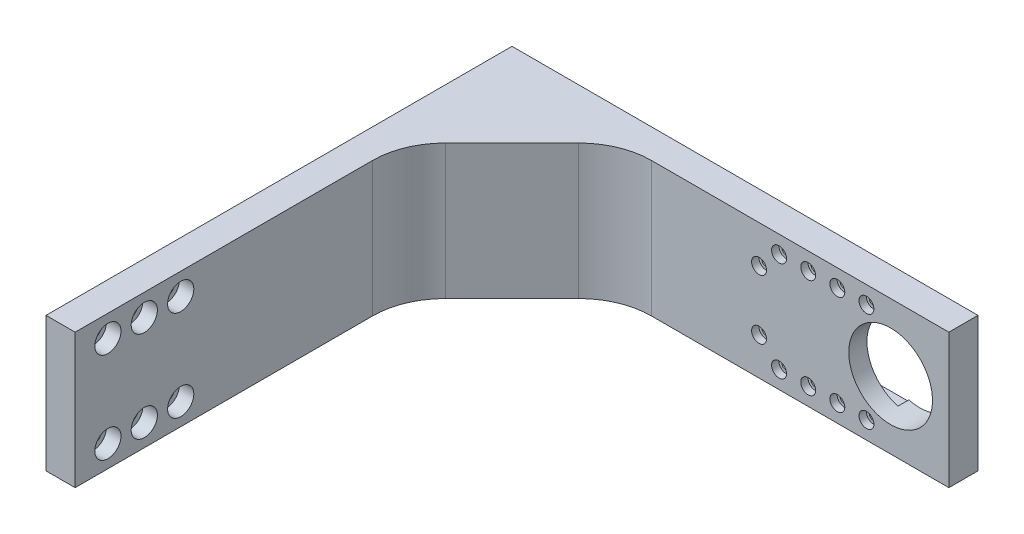
SolidWorks part; units mm, degrees
ref_plane "Front Plane" through (0, 0, 0) normal (0, 0, 1) x (1, 0, 0)
ref_plane "Top Plane" through (0, 0, 0) normal (0, 1, 0) x (1, 0, 0)
ref_plane "Right Plane" through (0, 0, 0) normal (1, 0, 0) x (0, 0, -1)
sketch "Sketch1" plane through (0, 0, 0) normal (0, 1, 0) x (1, 0, 0)
  line L0 (0, 0) -> (0, 128)
  line L1 (0, 128) -> (128, 128)
  line L2 (128, 128) -> (128, 120)
  line L3 (128, 120) -> (8, 120)
  line L4 (8, 120) -> (8, 0)
  line L5 (8, 0) -> (0, 0)
  dimension "D1" = 120
  dimension "D2" = 120
  dimension "D3" = 128
  dimension "D4" = 128
extrude "Boss-Extrude1" add sketch "Sketch1" along normal blind 37
sketch "Sketch2" plane through (0, 0, -128) normal (0, 0, -1) x (-1, 0, 0)
  line L0 (-128, 18.5) -> (-112, 18.5)
  line L1 (-128, 37) -> (-128, 0) construction
  circle A0 centre (-112, 18.5) radius 11.5
  dimension "D2" = 23
  dimension "D1" = 16
extrude "Cut-Extrude1" cut sketch "Sketch2" against normal up to next
sketch "Sketch3" plane through (0, 0, -128) normal (0, 0, -1) x (-1, 0, 0)
  line L0 (-128, 18.5) -> (-71.8119, 18.5)
  line L2 (-128, 37) -> (-128, 0) construction
  circle A0 centre (-105.36, 32.19) radius 1.25
  circle A1 centre (-97.36, 32.19) radius 1.25
  circle A2 centre (-89.36, 32.19) radius 1.25
  circle A3 centre (-81.36, 32.19) radius 1.25
  circle A4 centre (-81.36, 4.81) radius 1.25
  circle A5 centre (-89.36, 4.81) radius 1.25
  circle A6 centre (-97.36, 4.81) radius 1.25
  circle A7 centre (-105.36, 4.81) radius 1.25
  circle A8 centre (-75.86, 26.69) radius 1.25
  circle A9 centre (-75.86, 10.31) radius 1.25
  dimension "D3" = 2.5
  dimension "D6" = 2.5
  dimension "D7" = 2.5
  dimension "D1" = 4
extrude "Cut-Extrude2" cut sketch "Sketch3" against normal up to next contours A9 | A0 | A1 | A2 | A3 | A4 | A5 | A6 | A7 | A8
sketch "Sketch5" plane through (0, 0, -128) normal (0, 0, -1) x (-1, 0, 0)
  line L0 (-109, 7) -> (-109, 30)
  line L4 (-109, 30) -> (-71, 30)
  line L5 (-71, 30) -> (-71, 7)
  line L6 (-71, 7) -> (-109, 7)
  dimension "D3" = 23
  dimension "D4" = 38
  dimension "D5" = 38
extrude "Cut-Extrude3" cut sketch "Sketch5" against normal blind 3
sketch "Sketch6" plane through (71, 0, 0) normal (1, 0, 0) x (0, 0, -1)
  line L4 (128, 7) -> (128, 30)
  line L5 (128, 30) -> (125, 30)
  line L6 (125, 30) -> (125, 7)
  line L7 (125, 7) -> (128, 7)
  line L8 (128, 7) -> (128, 30)
  line L9 (128, 30) -> (125, 30)
  line L10 (125, 30) -> (125, 7)
  line L11 (125, 7) -> (128, 7)
  dimension "D1" = 0
extrude "Boss-Extrude2" add sketch "Sketch6" along normal blind 7.5
sketch "Sketch7" plane through (0, 0, -125) normal (0, 0, 1) x (1, 0, 0)
  circle A0 centre (75.86, 10.31) radius 1.25 construction
  circle A1 centre (75.86, 26.69) radius 1.25 construction
  circle A2 centre (75.86, 10.31) radius 1.25
  circle A3 centre (75.86, 26.69) radius 1.25
extrude "Cut-Extrude4" cut sketch "Sketch7" against normal up to next
sketch "Sketch8" plane through (0, 0, -120) normal (0, 0, 1) x (1, 0, 0)
  circle A0 centre (75.86, 10.31) radius 2.05
  circle A1 centre (75.86, 26.69) radius 2.05
  circle A2 centre (81.36, 32.19) radius 2.05
  circle A3 centre (89.36, 32.19) radius 2.05
  circle A4 centre (97.36, 32.19) radius 2.05
  circle A5 centre (105.36, 32.19) radius 2.05
  circle A6 centre (105.36, 4.81) radius 2.05
  circle A7 centre (97.36, 4.81) radius 2.05
  circle A8 centre (89.36, 4.81) radius 2.05
  circle A9 centre (81.36, 4.81) radius 2.05
  dimension "D1" = 4.1
  dimension "D2" = 4.1
  dimension "D3" = 4.1
  dimension "D4" = 4.1
  dimension "D5" = 4.1
  dimension "D6" = 4.1
  dimension "D7" = 4.1
  dimension "D8" = 4.1
  dimension "D9" = 4.1
  dimension "D10" = 4.1
extrude "Cut-Extrude5" cut sketch "Sketch8" against normal blind 2
sketch "Sketch9" plane through (8, 0, 0) normal (1, 0, 0) x (0, 0, -1)
  circle A0 centre (9, 6) radius 2.25
  circle A1 centre (19, 6) radius 2.25
  circle A2 centre (29, 6) radius 2.25
  circle A3 centre (29, 31) radius 2.25
  circle A4 centre (9, 31) radius 2.25
  circle A5 centre (19, 31) radius 2.25
  dimension "D3" = 4.5
  dimension "D4" = 3
extrude "Cut-Extrude6" cut sketch "Sketch9" against normal up to next contours A3 | A5 | A4 | A1 | A2 | A0
sketch "Sketch10" plane through (8, 0, 0) normal (1, 0, 0) x (0, 0, -1)
  circle A0 centre (9, 31) radius 3.6
  circle A1 centre (19, 31) radius 3.6
  circle A2 centre (29, 31) radius 3.6
  circle A3 centre (29, 6) radius 3.6
  circle A4 centre (19, 6) radius 3.6
  circle A5 centre (9, 6) radius 3.6
  dimension "D1" = 7.2
  dimension "D2" = 7.2
  dimension "D3" = 7.2
  dimension "D4" = 7.2
  dimension "D5" = 7.2
  dimension "D6" = 7.2
extrude "Cut-Extrude7" cut sketch "Sketch10" against normal blind 4
chamfer "Chamfer1" distance 30 angle 45 1 edges at (8, 18.5, -120)
fillet "Fillet4" radius 20 2 edges at (38, 18.5, -120) (8, 18.5, -90)
